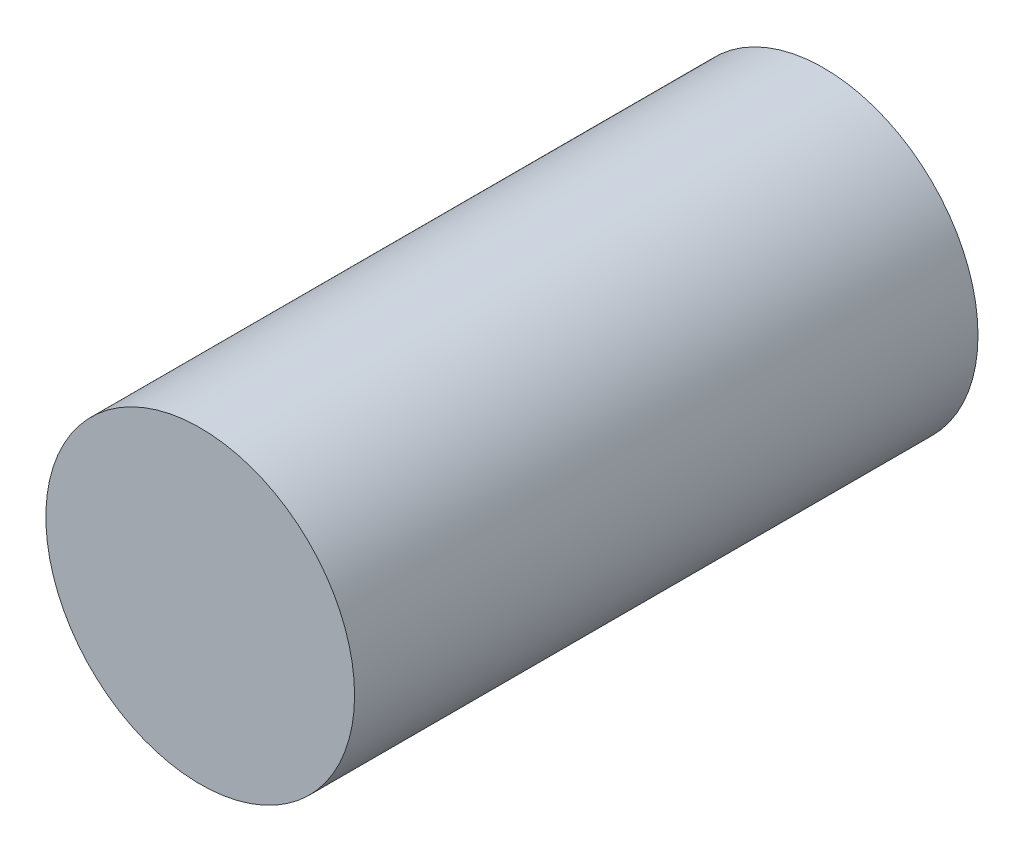
SolidWorks part; units mm, degrees
ref_plane "Front Plane" through (0, 0, 0) normal (0, 0, 1) x (1, 0, 0)
ref_plane "Top Plane" through (0, 0, 0) normal (0, 1, 0) x (1, 0, 0)
ref_plane "Right Plane" through (0, 0, 0) normal (1, 0, 0) x (0, 0, -1)
sketch "Sketch1" plane through (0, 0, 0) normal (0, 0, 1) x (1, 0, 0)
  circle A0 centre (0, 0) radius 9.904
extrude "Boss-Extrude1" add sketch "Sketch1" along normal blind 40
